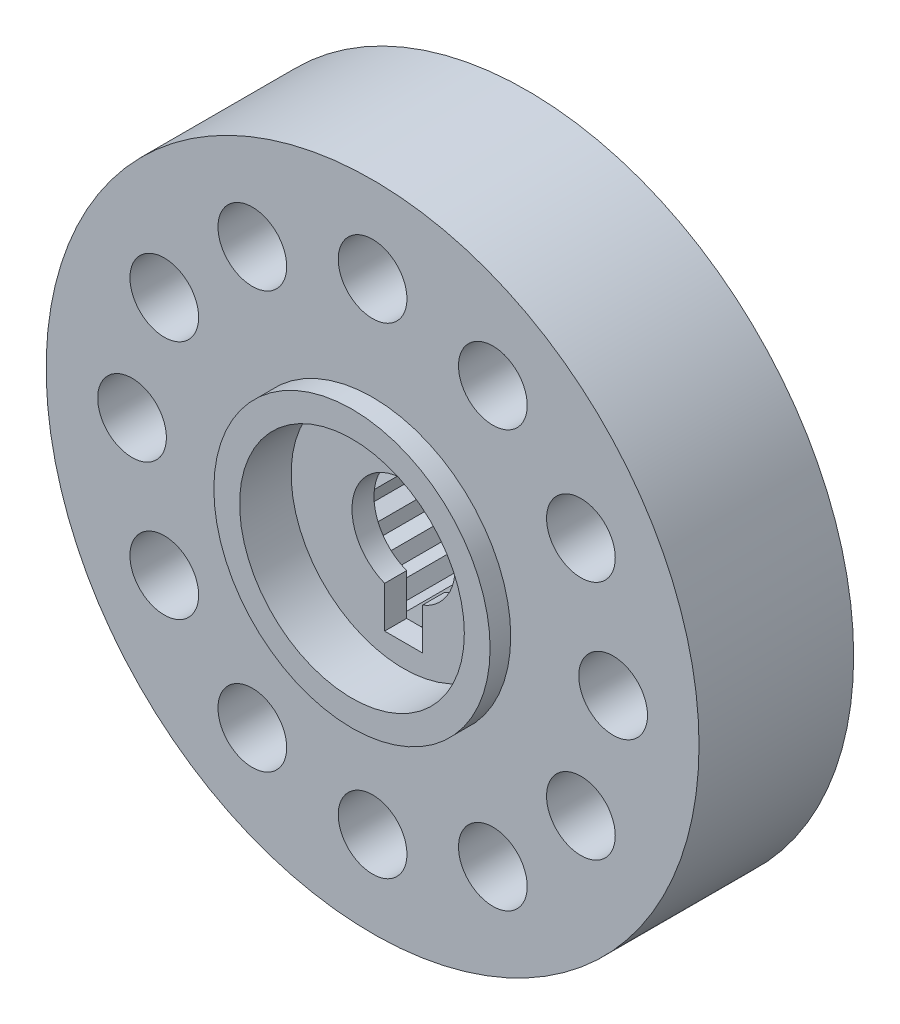
SolidWorks part; units mm, degrees
material "Custom Plastic"
ref_plane "Front Plane" through (0, 0, 0) normal (0, 0, 1) x (1, 0, 0)
ref_plane "Top Plane" through (0, 0, 0) normal (0, 1, 0) x (1, 0, 0)
ref_plane "Right Plane" through (0, 0, 0) normal (1, 0, 0) x (0, 0, -1)
sketch "base" plane through (0, 0, 0) normal (0, 0, 1) x (1, 0, 0)
  circle A0 centre (0, 0) radius 9.5
  dimension "D1" = 19
extrude "body" add sketch "base" along normal blind 4.5 contours A0
sketch "base 2" plane through (0, 0, 0) normal (0, 0, -1) x (-1, 0, 0)
  circle A0 centre (0, 0) radius 4.53
  dimension "D1" = 9.06
extrude "spline extrusion back" add sketch "base 2" along normal blind 1.34
sketch "base 3" plane through (0, 0, 4.5) normal (0, 0, 1) x (1, 0, 0)
  circle A0 centre (0, 0) radius 4.02
  circle A1 centre (0, 0) radius 3.27
  dimension "D1" = 8.04
  dimension "D2" = 6.54
extrude "spline extrusion front" add sketch "base 3" along normal blind 0.6
sketch "front base" plane through (0, 0, 4.5) normal (0, 0, 1) x (1, 0, 0)
  circle A0 centre (0, 0) radius 3.27
extrude "front recession" cut sketch "front base" against normal blind 0.9
sketch "spline profile" plane through (0, 0, -1.34) normal (0, 0, -1) x (-1, 0, 0)
  line L0 (0, 0) -> (0.7266, 5.7517) construction
  line L1 (0, 0) -> (-0.7806, 6.1791) construction
  line L2 (0, 0) -> (0, 5.6271) construction
  line L3 (-0.3259, 2.5795) -> (0, 2.85)
  line L4 (0, 2.85) -> (0.3259, 2.5795)
  line L5 (0.3259, 2.5795) -> (0.7088, 2.7605)
  line L6 (0.7088, 2.7605) -> (0.9571, 2.4174)
  line L7 (0.9571, 2.4174) -> (1.373, 2.4975)
  line L8 (1.373, 2.4975) -> (1.5282, 2.1034)
  line L9 (1.5282, 2.1034) -> (1.951, 2.0776)
  line L10 (1.951, 2.0776) -> (2.0033, 1.6573)
  line L11 (2.0033, 1.6573) -> (2.4063, 1.5271)
  line L12 (2.4063, 1.5271) -> (2.3526, 1.107)
  line L13 (2.3526, 1.107) -> (2.7105, 0.8807)
  line L14 (2.7105, 0.8807) -> (2.5539, 0.4872)
  line L15 (2.5539, 0.4872) -> (2.8444, 0.179)
  line L16 (2.8444, 0.179) -> (2.5949, -0.1633)
  line L17 (2.5949, -0.1633) -> (2.7995, -0.534)
  line L18 (2.7995, -0.534) -> (2.4727, -0.8034)
  line L19 (2.4727, -0.8034) -> (2.5788, -1.2135)
  line L20 (2.5788, -1.2135) -> (2.1953, -1.3931)
  line L21 (2.1953, -1.3931) -> (2.196, -1.8167)
  line L22 (2.196, -1.8167) -> (1.7798, -1.8953)
  line L23 (1.7798, -1.8953) -> (1.6752, -2.3057)
  line L24 (1.6752, -2.3057) -> (1.2526, -2.2784)
  line L25 (1.2526, -2.2784) -> (1.0492, -2.6499)
  line L26 (1.0492, -2.6499) -> (0.6466, -2.5183)
  line L27 (0.6466, -2.5183) -> (0.3572, -2.8275)
  line L28 (0.3572, -2.8275) -> (0, -2.6)
  line L29 (0, -2.6) -> (-0.3572, -2.8275)
  line L30 (-0.3572, -2.8275) -> (-0.6466, -2.5183)
  line L31 (-0.6466, -2.5183) -> (-1.0492, -2.6499)
  line L32 (-1.0492, -2.6499) -> (-1.2526, -2.2784)
  line L33 (-1.2526, -2.2784) -> (-1.6752, -2.3057)
  line L34 (-1.6752, -2.3057) -> (-1.7798, -1.8953)
  line L35 (-1.7798, -1.8953) -> (-2.196, -1.8167)
  line L36 (-2.196, -1.8167) -> (-2.1953, -1.3931)
  line L37 (-2.1953, -1.3931) -> (-2.5788, -1.2135)
  line L38 (-2.5788, -1.2135) -> (-2.4727, -0.8034)
  line L39 (-2.4727, -0.8034) -> (-2.7995, -0.534)
  line L40 (-2.7995, -0.534) -> (-2.5949, -0.1633)
  line L41 (-2.5949, -0.1633) -> (-2.8444, 0.179)
  line L42 (-2.8444, 0.179) -> (-2.5539, 0.4872)
  line L43 (-2.5539, 0.4872) -> (-2.7105, 0.8807)
  line L44 (-2.7105, 0.8807) -> (-2.3526, 1.107)
  line L45 (-2.3526, 1.107) -> (-2.4063, 1.5271)
  line L46 (-2.4063, 1.5271) -> (-2.0033, 1.6573)
  line L47 (-2.0033, 1.6573) -> (-1.951, 2.0776)
  line L48 (-1.951, 2.0776) -> (-1.5282, 2.1034)
  line L49 (-1.5282, 2.1034) -> (-1.373, 2.4975)
  line L50 (-1.373, 2.4975) -> (-0.9571, 2.4174)
  line L51 (-0.9571, 2.4174) -> (-0.7088, 2.7605)
  line L52 (-0.7088, 2.7605) -> (-0.3259, 2.5795)
  circle A0 centre (0, 0) radius 2.6 construction
  circle A1 centre (0, 0) radius 2.85 construction
  point P6 (-0.3259, 2.5795)
  point P11 (0.3259, 2.5795)
  point P89 (0, 0)
  dimension "D1" = 5.7
  dimension "D2" = 5.2
  dimension "D3" = 7.2
  dimension "D4" = 7.2
  dimension "D5" = 25
extrude "spline" cut sketch "spline profile" against normal blind 4.3
sketch "center screw hole sketch" plane through (0, 0, 3.6) normal (0, 0, 1) x (1, 0, 0)
  line L6 (0, -1.5) -> (4.7643, -1.5) construction
  line L7 (0, -2.6) -> (0, 0.4989) construction
  line L8 (0.55, -2.6) -> (0.55, -1.3955)
  line L9 (-0.55, -2.6) -> (0.55, -2.6)
  line L10 (-0.55, -1.3955) -> (-0.55, -2.6)
  circle A0 centre (0, 0) radius 1.5
  dimension "D1" = 3
  dimension "D2" = 1.1
  dimension "D3" = 1.1
extrude "center screw hole" cut sketch "center screw hole sketch" against normal up to surface (0.64 mm away)
sketch "screw hole sketch" plane through (0, 0, 4.5) normal (0, 0, 1) x (1, 0, 0)
  circle A0 centre (0, 0) radius 7 construction
  circle A1 centre (0, 7) radius 1
  circle A2 centre (3.5, 6.0622) radius 1
  circle A3 centre (6.0622, 3.5) radius 1
  circle A4 centre (7, 0) radius 1
  circle A5 centre (6.0622, -3.5) radius 1
  circle A6 centre (3.5, -6.0622) radius 1
  circle A7 centre (0, -7) radius 1
  circle A8 centre (-3.5, -6.0622) radius 1
  circle A9 centre (-6.0622, -3.5) radius 1
  circle A10 centre (-7, 0) radius 1
  circle A11 centre (-6.0622, 3.5) radius 1
  circle A12 centre (-3.5, 6.0622) radius 1
  point P29 (0, 0)
  dimension "D1" = 14
  dimension "D2" = 2
  dimension "D3" = 12
extrude "screw holes" cut sketch "screw hole sketch" against normal through all
